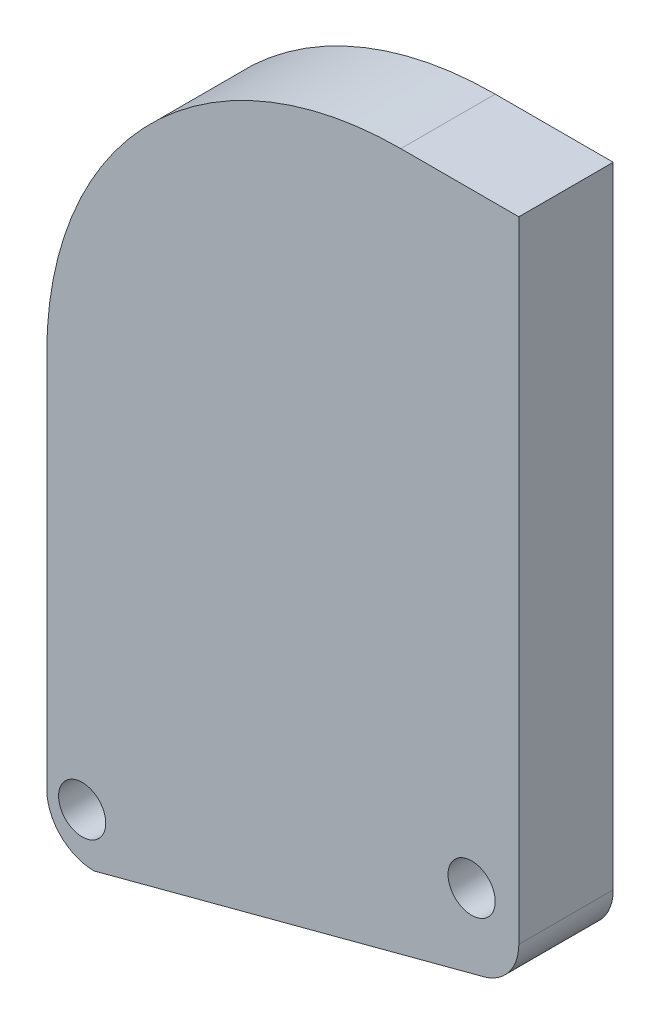
SolidWorks part; units mm, degrees
ref_plane "Front Plane" through (0, 0, 0) normal (0, 0, 1) x (1, 0, 0)
ref_plane "Top Plane" through (0, 0, 0) normal (0, 1, 0) x (1, 0, 0)
ref_plane "Right Plane" through (0, 0, 0) normal (1, 0, 0) x (0, 0, -1)
sketch "Sketch1" plane through (0, 0, 0) normal (0, 0, 1) x (1, 0, 0)
  line L1 (0, 0) -> (-5, 0)
  line L2 (0, 0) -> (0, -26.6942)
  line L4 (-20, -15) -> (-20, -31)
  line L6 (-18, -31) -> (-18.5, -31)
  line L7 (-18, -33) -> (-1.488, -28.6276)
  arc A0 (-5, 0) -> (-20, -15) centre (-5, -15) ccw
  arc A2 (-18, -33) -> (-20, -31) centre (-18, -31) cw
  circle A3 centre (-18.5, -31) radius 1
  arc A5 (0, -26.6942) -> (-1.488, -28.6276) centre (-2, -26.6942) cw
  circle A6 centre (-2, -25.6284) radius 1
  point P7 (-20, 0)
  dimension "D3" = 15
  dimension "D6" = 0.5
  dimension "D7" = 2
  dimension "D9" = 2
  dimension "D10" = 2
  dimension "D1" = 20
extrude "Boss-Extrude1" add sketch "Sketch1" along normal blind 4
